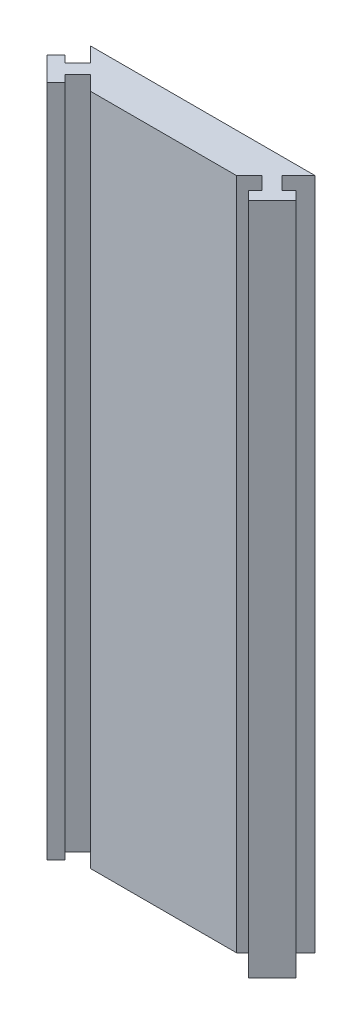
SolidWorks part; units mm, degrees
ref_plane "Front Plane" through (0, 0, 0) normal (0, 0, 1) x (1, 0, 0)
ref_plane "Top Plane" through (0, 0, 0) normal (0, 1, 0) x (1, 0, 0)
ref_plane "Right Plane" through (0, 0, 0) normal (1, 0, 0) x (0, 0, -1)
sketch "Sketch1" plane through (0, 0, 0) normal (0, 1, 0) x (1, 0, 0)
  line L1 (-52.4677, -17.0275) -> (-12.4677, -17.0275)
  line L2 (-52.4677, -17.0275) -> (-52.4677, -10.0275)
  line L3 (-52.4677, -10.0275) -> (-12.4677, -10.0275)
  line L4 (-12.4677, -17.0275) -> (-12.4677, -10.0275)
  dimension "D1" = 7
  dimension "D2" = 40
extrude "Boss-Extrude3" add sketch "Sketch1" along normal blind 120
sketch "Sketch6" plane through (0, 120, 0) normal (0, 1, 0) x (1, 0, 0)
  line L0 (-52.4677, -17.0275) -> (-52.4677, -10.0275)
  line L1 (-52.4677, -10.0275) -> (-45.4677, -17.0275)
  line L2 (-52.4677, -17.0275) -> (-12.4677, -17.0275) construction
  line L3 (-45.4677, -17.0275) -> (-52.4677, -17.0275)
extrude "Cut-Extrude3" cut sketch "Sketch6" against normal blind 120
sketch "Sketch7" plane through (0, 120, 0) normal (0, 1, 0) x (1, 0, 0)
  line L0 (-12.4677, -17.0275) -> (-12.4677, -10.0275)
  line L1 (-12.4677, -10.0275) -> (-19.4677, -17.0275)
  line L2 (-45.4677, -17.0275) -> (-12.4677, -17.0275) construction
  line L3 (-19.4677, -17.0275) -> (-12.4677, -17.0275)
extrude "Cut-Extrude4" cut sketch "Sketch7" against normal blind 120
sketch "Sketch8" plane through (0, 120, 0) normal (0, 1, 0) x (1, 0, 0)
  line L0 (-49.8161, -12.6791) -> (-52.1142, -14.9772)
  line L1 (-45.4677, -17.0275) -> (-52.4677, -10.0275) construction
  line L2 (-52.1142, -14.9772) -> (-53.3516, -13.7398)
  line L3 (-53.3516, -13.7398) -> (-54.9426, -15.3308)
  line L4 (-54.9426, -15.3308) -> (-50.7, -19.5734)
  line L5 (-50.7, -19.5734) -> (-49.109, -17.9824)
  line L6 (-49.109, -17.9824) -> (-50.3464, -16.745)
  line L7 (-50.3464, -16.745) -> (-48.0483, -14.4469)
  line L8 (-48.0483, -14.4469) -> (-49.8161, -12.6791)
  dimension "D1" = 6
  dimension "D2" = 1.75
  dimension "D3" = 1.75
  dimension "D4" = 2.25
  dimension "D5" = 3.25
  dimension "D6" = 3.25
  dimension "D7" = 3.75
extrude "Boss-Extrude4" add sketch "Sketch8" against normal blind 120
sketch "Sketch9" plane through (0, 120, 0) normal (0, 1, 0) x (1, 0, 0)
  line L0 (-17.1724, -14.7321) -> (-14.8743, -17.0302)
  line L1 (-12.4677, -10.0275) -> (-19.4677, -17.0275) construction
  line L2 (-14.8743, -17.0302) -> (-16.1117, -18.2677)
  line L3 (-16.1117, -18.2677) -> (-14.5207, -19.8587)
  line L4 (-14.5207, -19.8587) -> (-10.2781, -15.616)
  line L5 (-10.2781, -15.616) -> (-11.8691, -14.025)
  line L6 (-11.8691, -14.025) -> (-13.1065, -15.2625)
  line L7 (-13.1065, -15.2625) -> (-15.4046, -12.9644)
  line L8 (-15.4046, -12.9644) -> (-17.1724, -14.7321)
  dimension "D1" = 6
  dimension "D2" = 2.25
  dimension "D3" = 2.25
  dimension "D4" = 1.75
  dimension "D5" = 1.75
  dimension "D6" = 3.25
extrude "Boss-Extrude5" add sketch "Sketch9" against normal blind 120
